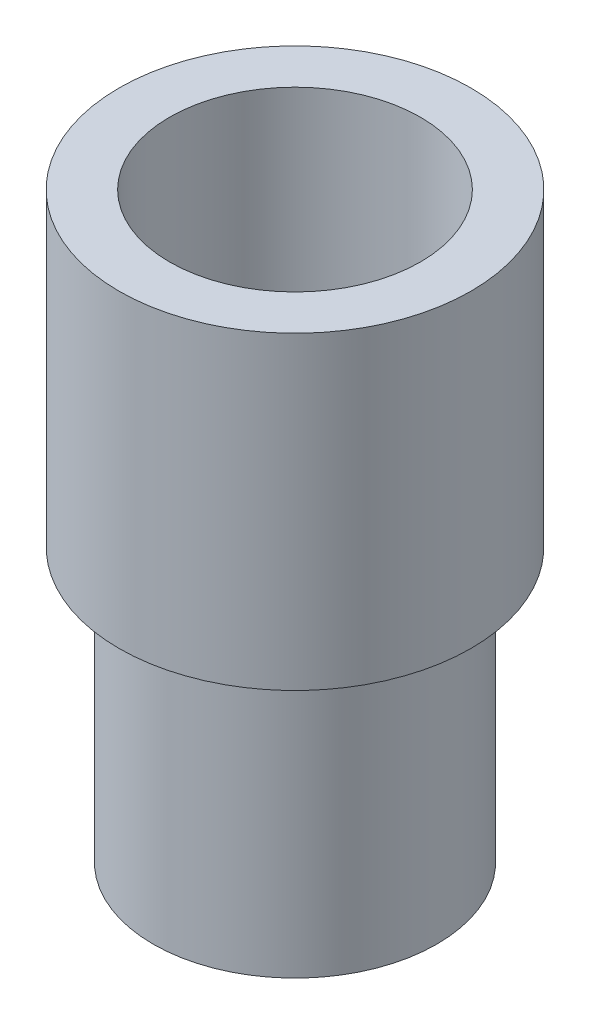
SolidWorks part; units mm, degrees
material "AISI 304"
ref_plane "Front Plane" through (0, 0, 0) normal (0, 0, 1) x (1, 0, 0)
ref_plane "Top Plane" through (0, 0, 0) normal (0, 1, 0) x (1, 0, 0)
ref_plane "Right Plane" through (0, 0, 0) normal (1, 0, 0) x (0, 0, -1)
sketch "Sketch1" plane through (0, 0, 0) normal (0, 0, 1) x (1, 0, 0)
  line L0 (0, 0) -> (0, 65) construction
  line L2 (13.9954, 0) -> (15.8242, 0)
  line L3 (13.9954, 0) -> (13.9954, 30.48)
  line L4 (13.9954, 30.48) -> (15.8242, 30.48)
  line L5 (15.8242, 0) -> (15.8242, 30.48)
  line L6 (13.9954, 30.48) -> (19.6342, 30.48)
  line L7 (13.9954, 30.48) -> (13.9954, 65)
  line L8 (13.9954, 65) -> (19.6342, 65)
  line L9 (19.6342, 30.48) -> (19.6342, 65)
  line L10 (13.9954, 40.48) -> (0, 40.48)
  line L11 (13.9954, 40.48) -> (13.9954, 30.48)
  line L12 (13.9954, 30.48) -> (0, 30.48)
  line L13 (0, 40.48) -> (0, 30.48)
  dimension "D1" = 65
  dimension "D2" = 31.6484
  dimension "D3" = 1.8288
  dimension "D4" = 30.48
  dimension "D5" = 3.81
  dimension "D6" = 10
revolve "Revolve1" add sketch "Sketch1" angle 360 about L0
